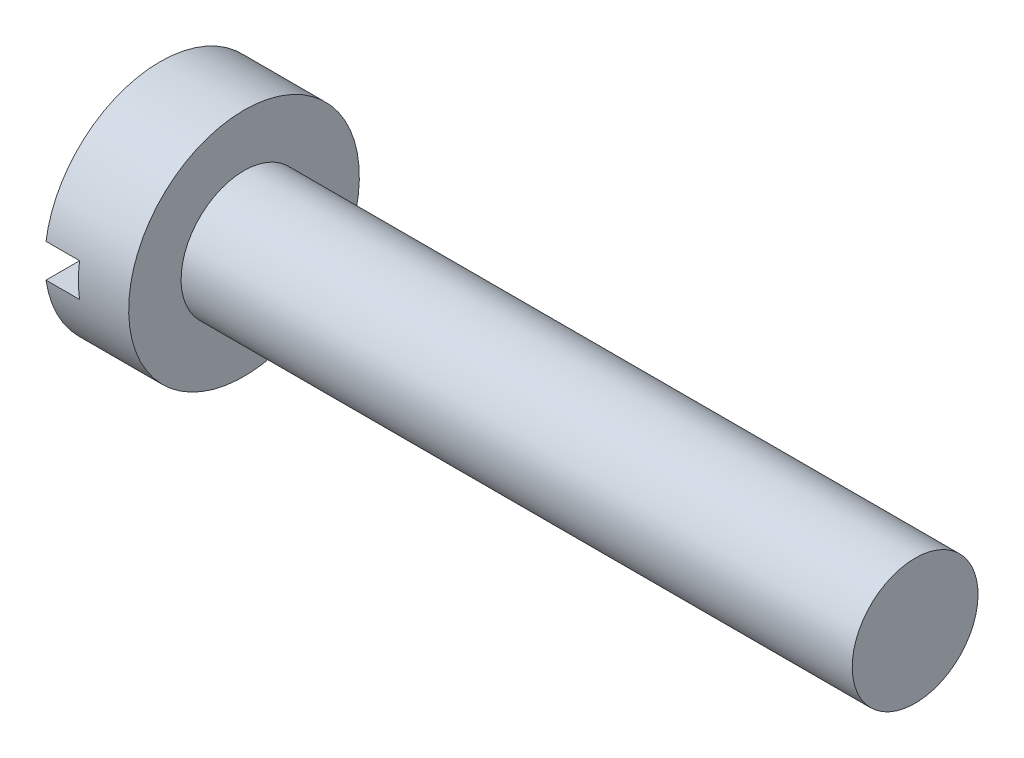
SolidWorks part; units mm, degrees
material "Plain Carbon Steel"
ref_plane "Front Plane" through (0, 0, 0) normal (0, 0, 1) x (1, 0, 0)
ref_plane "Top Plane" through (0, 0, 0) normal (0, 1, 0) x (1, 0, 0)
ref_plane "Right Plane" through (0, 0, 0) normal (1, 0, 0) x (0, 0, -1)
sketch "Sketch1" plane through (0, 0, 0) normal (0, 0, 1) x (1, 0, 0)
  line L0 (0, 0) -> (0, 2.75)
  line L1 (0, 2.75) -> (2, 2.75)
  line L2 (2, 2.75) -> (2, 1.5)
  line L3 (2, 1.5) -> (18, 1.5)
  line L4 (18, 1.5) -> (18, 0)
  line L5 (18, 0) -> (0, 0) construction
  line L6 (0, 0) -> (18, 0)
  dimension "D1" = 3
  dimension "D2" = 16
  dimension "D3" = 5.5
  dimension "D4" = 2
revolve "Revolve1" add sketch "Sketch1" angle 360 about L5
sketch "Sketch2" plane through (0, 0, 0) normal (-1, 0, 0) x (0, 0, 1)
  line L0 (2.75, 0) -> (-2.75, 0) construction
  line L1 (-2.75, 0.4) -> (2.75, 0.4)
  line L2 (-2.75, 0.4) -> (-2.75, -0.4)
  line L3 (-2.75, -0.4) -> (2.75, -0.4)
  line L4 (2.75, 0.4) -> (2.75, -0.4)
  circle A0 centre (0, 0) radius 2.75 construction
  dimension "D1" = 0.8
extrude "Cut-Extrude1" cut sketch "Sketch2" against normal blind 0.8
